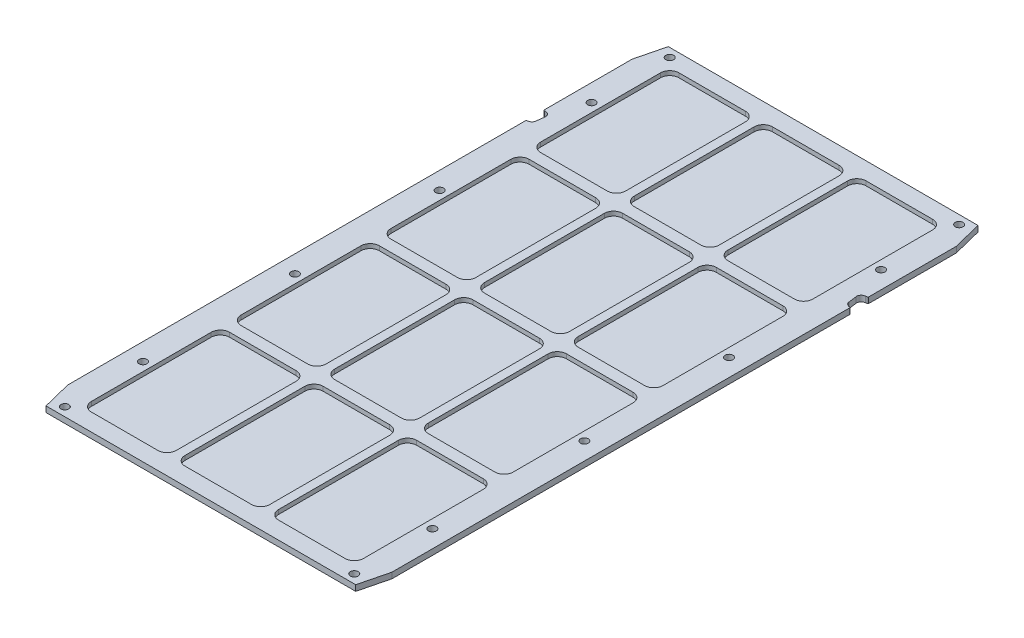
SolidWorks part; units mm, degrees
other "Markup1"
sketch "Sketch7" plane through (-56, 2, 107.5) normal (-0.0005, 0.9738, 0.2273) x (1, -0.0006, 0.0044)
material "Custom Plastic"
ref_plane "Front Plane" through (0, 0, 0) normal (0, 0, 1) x (1, 0, 0)
ref_plane "Top Plane" through (0, 0, 0) normal (0, 1, 0) x (1, 0, 0)
ref_plane "Right Plane" through (0, 0, 0) normal (1, 0, 0) x (0, 0, -1)
sketch "Sketch1" plane through (0, 0, 0) normal (0, 1, 0) x (1, 0, 0)
  line L1 (56, -107.5) -> (-56, -107.5)
  line L2 (56, -107.5) -> (56, 107.5)
  line L3 (56, 107.5) -> (-56, 107.5)
  line L4 (-56, -107.5) -> (-56, 107.5)
  line L5 (56, -107.5) -> (-56, 107.5) construction
  line L6 (56, 107.5) -> (-56, -107.5) construction
  point P0 (0, 0)
  dimension "D1" = 112
  dimension "D2" = 215
extrude "Boss-Extrude1" add sketch "Sketch1" along normal blind 2
sketch "Sketch2" plane through (0, 2, 0) normal (0, 1, 0) x (1, 0, 0)
  line L0 (-56, 107.5) -> (-56, -107.5) construction
  line L1 (-47, 101.5) -> (-17.6667, 101.5)
  line L2 (-47, 101.5) -> (-47, 53.75)
  line L3 (-47, 53.75) -> (-17.6667, 53.75)
  line L4 (-17.6667, 101.5) -> (-17.6667, 53.75)
  line L5 (-47, 101.5) -> (-17.6667, 53.75) construction
  line L6 (-47, 53.75) -> (-17.6667, 101.5) construction
  line L11 (56, 107.5) -> (-56, 107.5) construction
  line L22 (-32.3333, 77.625) -> (-32.3333, 0) construction
  line L23 (32.3333, 0) -> (-32.3333, 0) construction
  line L24 (0, 0) -> (0, 77.625) construction
  line L25 (-17.6667, 49.75) -> (-47, 49.75)
  line L26 (-17.6667, 49.75) -> (-17.6667, 2)
  line L31 (-17.6667, 2) -> (-47, 2)
  line L32 (-47, 49.75) -> (-47, 2)
  line L37 (-17.6667, 49.75) -> (-47, 2) construction
  line L38 (-17.6667, 2) -> (-47, 49.75) construction
  line L39 (32.3333, 0) -> (32.3333, 77.625) construction
  line L44 (14.6667, 101.5) -> (-14.6667, 101.5)
  line L45 (14.6667, 101.5) -> (14.6667, 53.75)
  line L50 (14.6667, 53.75) -> (-14.6667, 53.75)
  line L51 (-14.6667, 101.5) -> (-14.6667, 53.75)
  line L56 (14.6667, 101.5) -> (-14.6667, 53.75) construction
  line L57 (14.6667, 53.75) -> (-14.6667, 101.5) construction
  line L62 (14.6667, 49.75) -> (-14.6667, 49.75)
  line L63 (14.6667, 49.75) -> (14.6667, 2)
  line L68 (14.6667, 2) -> (-14.6667, 2)
  line L69 (-14.6667, 49.75) -> (-14.6667, 2)
  line L74 (14.6667, 49.75) -> (-14.6667, 2) construction
  line L75 (14.6667, 2) -> (-14.6667, 49.75) construction
  line L80 (-17.6667, -2) -> (-47, -2)
  line L81 (47, 53.75) -> (17.6667, 53.75)
  line L82 (47, 53.75) -> (47, 101.5)
  line L83 (47, 101.5) -> (17.6667, 101.5)
  line L85 (17.6667, 53.75) -> (17.6667, 101.5)
  line L86 (47, 53.75) -> (17.6667, 101.5) construction
  line L87 (47, 101.5) -> (17.6667, 53.75) construction
  line L88 (47, 2) -> (17.6667, 2)
  line L89 (47, 2) -> (47, 49.75)
  line L90 (47, 49.75) -> (17.6667, 49.75)
  line L91 (17.6667, 2) -> (17.6667, 49.75)
  line L92 (47, 2) -> (17.6667, 49.75) construction
  line L93 (47, 49.75) -> (17.6667, 2) construction
  line L94 (-47, -49.75) -> (-47, -2)
  line L95 (-17.6667, -49.75) -> (-47, -49.75)
  line L96 (-17.6667, -49.75) -> (-17.6667, -2)
  line L97 (14.6667, -2) -> (-14.6667, -2)
  line L98 (-14.6667, -49.75) -> (-14.6667, -2)
  line L99 (14.6667, -49.75) -> (-14.6667, -49.75)
  line L100 (14.6667, -49.75) -> (14.6667, -2)
  line L101 (47, -49.75) -> (17.6667, -49.75)
  line L102 (17.6667, -2) -> (17.6667, -49.75)
  line L103 (47, -2) -> (17.6667, -2)
  line L104 (47, -2) -> (47, -49.75)
  line L105 (47, -101.5) -> (17.6667, -101.5)
  line L106 (17.6667, -53.75) -> (17.6667, -101.5)
  line L107 (47, -53.75) -> (17.6667, -53.75)
  line L108 (47, -53.75) -> (47, -101.5)
  line L109 (14.6667, -53.75) -> (-14.6667, -53.75)
  line L110 (-14.6667, -101.5) -> (-14.6667, -53.75)
  line L111 (14.6667, -101.5) -> (-14.6667, -101.5)
  line L112 (14.6667, -101.5) -> (14.6667, -53.75)
  line L113 (-47, -53.75) -> (-17.6667, -53.75)
  line L114 (-17.6667, -101.5) -> (-17.6667, -53.75)
  line L115 (-47, -101.5) -> (-17.6667, -101.5)
  line L116 (-47, -101.5) -> (-47, -53.75)
  point P0 (-32.3333, 77.625)
  point P9 (-32.3333, 25.875)
  point P12 (0, 0)
  point P24 (0, 25.875)
  point P35 (32.3333, 25.875)
  dimension "D1" = 9
  dimension "D2" = 6
  dimension "D3" = 4
  dimension "D4" = 2
  dimension "D5" = 3
extrude "Cut-Extrude1" cut sketch "Sketch2" against normal blind 1.5
sketch "Sketch3" plane through (0, 2, 0) normal (0, 1, 0) x (1, 0, 0)
  line L0 (-56, 107.5) -> (-53.5, 107.5)
  line L1 (56, 107.5) -> (-56, 107.5) construction
  line L2 (-53.5, 107.5) -> (-56, 97.5)
  line L3 (-56, 107.5) -> (-56, -107.5) construction
  line L4 (-56, 97.5) -> (-56, 107.5)
  line L5 (56, 107.5) -> (53.5, 107.5)
  line L6 (53.5, 107.5) -> (56, 97.5)
  line L7 (56, -107.5) -> (56, 107.5) construction
  line L8 (56, 97.5) -> (56, 107.5)
  line L9 (56, -107.5) -> (56, -97.5)
  line L10 (56, -97.5) -> (53.5, -107.5)
  line L12 (53.5, -107.5) -> (56, -107.5)
  line L13 (-56, -107.5) -> (-56, -97.5)
  line L14 (-56, -97.5) -> (-53.5, -107.5)
  line L15 (-53.5, -107.5) -> (-56, -107.5)
  dimension "D1" = 10
  dimension "D2" = 2.5
extrude "Cut-Extrude2" cut sketch "Sketch3" against normal through all
sketch "Sketch4" plane through (0, 2, 0) normal (0, 1, 0) x (1, 0, 0)
  line L0 (50, 0) -> (-50, 0) construction
  line L1 (-50, 25) -> (-50, -25) construction
  line L2 (-56, 97.5) -> (-56, -97.5) construction
  line L3 (53.5, 107.5) -> (-53.5, 107.5) construction
  line L5 (-53.5, -107.5) -> (53.5, -107.5) construction
  line L7 (-50, -25) -> (-50, -97.5) construction
  line L8 (-50, -97.5) -> (-50, -104.5) construction
  line L9 (0, -1.1) -> (0, 1.1) construction
  circle A0 centre (-50, 104.5) radius 1.35
  circle A5 centre (-50, -104.5) radius 1.35
  circle A7 centre (50, -104.5) radius 1.35
  circle A9 centre (50, -25) radius 1.35
  circle A10 centre (50, 25) radius 1.35
  circle A12 centre (50, 104.5) radius 1.35
  circle A13 centre (-50, 77.5) radius 1.35
  circle A14 centre (-50, 25) radius 1.35
  circle A15 centre (-50, -25) radius 1.35
  circle A16 centre (-50, -77.5) radius 1.35
  circle A17 centre (50, -77.5) radius 1.35
  circle A18 centre (50, 77.5) radius 1.35
  point P4 (0, 0)
  point P8 (-50, 0)
  point P24 (-50, 0)
  dimension "D1" = 2.7
  dimension "D6" = 3
  dimension "D8" = 6
  dimension "D2" = 6
  dimension "D3" = 3
  dimension "D5" = 10
extrude "Cut-Extrude3" cut sketch "Sketch4" against normal through all
fillet "Fillet1" radius 3.175 45 edges at (14.6667, 1.25, 53.75) (47, 1.25, 53.75) (47, 1.25, 2) (14.6667, 1.25, 2) (14.6667, 1.25, -49.75) (47, 1.25, -49.75) (-17.6667, 1.25, -53.75) (-17.6667, 1.25, -2) (-17.6667, 1.25, 49.75) (-17.6667, 1.25, 101.5) (14.6667, 1.25, 49.75) (14.6667, 1.25, -53.75) (14.6667, 1.25, -2) (47, 1.25, -53.75) (47, 1.25, -2) (47, 1.25, 49.75) (47, 1.25, 101.5) (14.6667, 1.25, 101.5) (-47, 1.25, 53.75) (-14.6667, 1.25, 53.75) (17.6667, 1.25, 53.75) (17.6667, 1.25, 2) (-14.6667, 1.25, 2) (-47, 1.25, 2) (17.6667, 1.25, -49.75) (-14.6667, 1.25, -49.75) (-47, 1.25, -49.75) (17.6667, 1.25, 49.75) (17.6667, 1.25, 101.5) (-14.6667, 1.25, 101.5) (-14.6667, 1.25, 49.75) (-14.6667, 1.25, -2) (17.6667, 1.25, -2) (17.6667, 1.25, -53.75) (-14.6667, 1.25, -53.75) (-47, 1.25, -53.75) (-47, 1.25, -2) (-47, 1.25, 49.75) (-47, 1.25, 101.5) (17.6667, 1.25, -101.5) (-14.6667, 1.25, -101.5) (-47, 1.25, -101.5) (47, 1.25, -101.5) (14.6667, 1.25, -101.5) (-17.6667, 1.25, -101.5)
fillet "Fillet2" radius 3.175 3 edges at (-17.6667, 1.25, -49.75) (-17.6667, 1.25, 2) (-17.6667, 1.25, 53.75)
sketch "Sketch9" plane through (0, 2, 0) normal (0, 1, 0) x (1, 0, 0)
  line L0 (-56, 66.9612) -> (-55.251, 66.9291)
  line L1 (-56, 97.5) -> (-56, -97.5) construction
  line L3 (-53.745, 65.1371) -> (-54.1127, 62.3276)
  line L4 (-56, 66.9612) -> (-57.5, 66.9612)
  line L5 (-57.5, 66.9612) -> (-57.5, 60.0888)
  line L6 (-57.5, 60.0888) -> (-56.927, 60.0888)
  line L7 (0, -1.1) -> (0, 1.1) construction
  line L8 (57.5, 66.9612) -> (57.5, 60.0888)
  line L9 (56, 66.9612) -> (57.5, 66.9612)
  line L10 (56, 66.9612) -> (55.251, 66.9291)
  line L11 (53.745, 65.1371) -> (54.1127, 62.3276)
  line L12 (57.5, 60.0888) -> (56.927, 60.0888)
  line L13 (-1.1, 0) -> (1.1, 0) construction
  line L14 (56, -66.9612) -> (57.5, -66.9612) construction
  line L15 (56, -66.9612) -> (55.251, -66.9291) construction
  line L16 (53.745, -65.1371) -> (54.1127, -62.3276) construction
  line L17 (57.5, -60.0888) -> (56.927, -60.0888) construction
  line L18 (57.5, -66.9612) -> (57.5, -60.0888) construction
  line L19 (-57.5, -66.9612) -> (-57.5, -60.0888) construction
  line L20 (-56, -66.9612) -> (-57.5, -66.9612) construction
  line L21 (-56, -66.9612) -> (-55.251, -66.9291) construction
  line L22 (-53.745, -65.1371) -> (-54.1127, -62.3276) construction
  line L23 (-57.5, -60.0888) -> (-56.927, -60.0888) construction
  arc A0 (-55.251, 66.9291) -> (-53.745, 65.1371) centre (-55.3191, 65.3431) cw
  arc A1 (-54.1127, 62.3276) -> (-55.8057, 60.9505) centre (-55.6868, 62.5336) cw
  arc A2 (-55.8057, 60.9505) -> (-56.927, 60.0888) centre (-55.9355, 59.959) ccw
  arc A3 (55.251, 66.9291) -> (53.745, 65.1371) centre (55.3191, 65.3431) ccw
  arc A4 (54.1127, 62.3276) -> (55.8057, 60.9505) centre (55.6868, 62.5336) ccw
  arc A5 (55.8057, 60.9505) -> (56.927, 60.0888) centre (55.9355, 59.959) cw
  arc A6 (55.251, -66.9291) -> (53.745, -65.1371) centre (55.3191, -65.3431) cw construction
  arc A7 (54.1127, -62.3276) -> (55.8057, -60.9505) centre (55.6868, -62.5336) cw construction
  arc A8 (55.8057, -60.9505) -> (56.927, -60.0888) centre (55.9355, -59.959) ccw construction
  arc A9 (-55.251, -66.9291) -> (-53.745, -65.1371) centre (-55.3191, -65.3431) ccw construction
  arc A10 (-54.1127, -62.3276) -> (-55.8057, -60.9505) centre (-55.6868, -62.5336) ccw construction
  arc A11 (-55.8057, -60.9505) -> (-56.927, -60.0888) centre (-55.9355, -59.959) cw construction
  dimension "D2" = 1
  dimension "D1" = 1.5
extrude "Cut-Extrude4" cut sketch "Sketch9" against normal through all
fillet "Fillet3" radius 0.3 4 edges at (56, 1, -66.9612) (56, 1, -60.9569) (-56, 1, -60.9569) (-56, 1, -66.9612)
